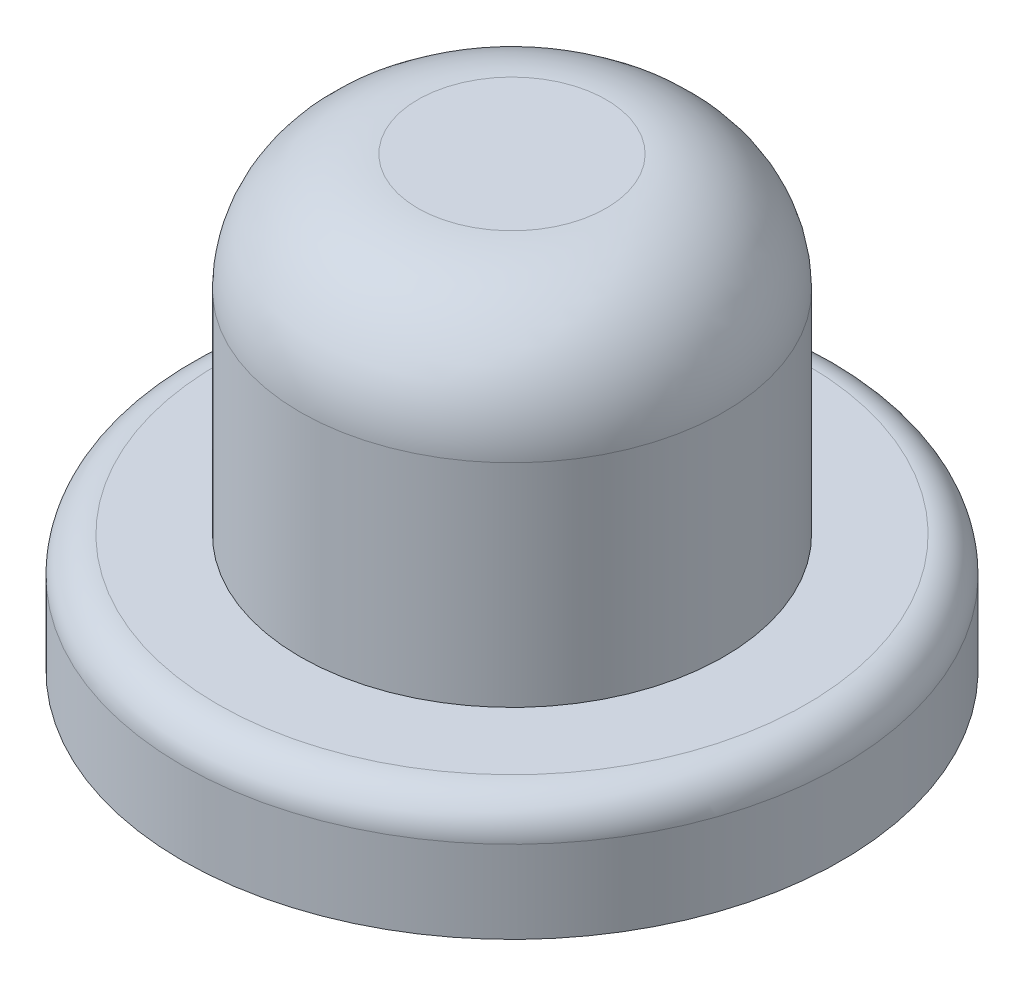
SolidWorks part; units mm, degrees
ref_plane "前视基准面" through (0, 0, 0) normal (0, 0, 1) x (1, 0, 0)
ref_plane "上视基准面" through (0, 0, 0) normal (0, 1, 0) x (1, 0, 0)
ref_plane "右视基准面" through (0, 0, 0) normal (1, 0, 0) x (0, 0, -1)
sketch "草图1" plane through (0, 0, 0) normal (0, 1, 0) x (1, 0, 0)
  circle A0 centre (0, 0) radius 2.8
  dimension "D1" = 5.6
extrude "凸台-拉伸2" add sketch "草图1" along normal blind 1
sketch "草图2" plane through (0, 1, 0) normal (0, 1, 0) x (1, 0, 0)
  circle A0 centre (0, 0) radius 1.8
  dimension "D1" = 3.6
extrude "凸台-拉伸3" add sketch "草图2" along normal blind 2.8
fillet "圆角1" radius 1 1 edges at (0, 3.8, 1.8)
fillet "圆角2" radius 0.3 1 edges at (0, 1, 2.8)
